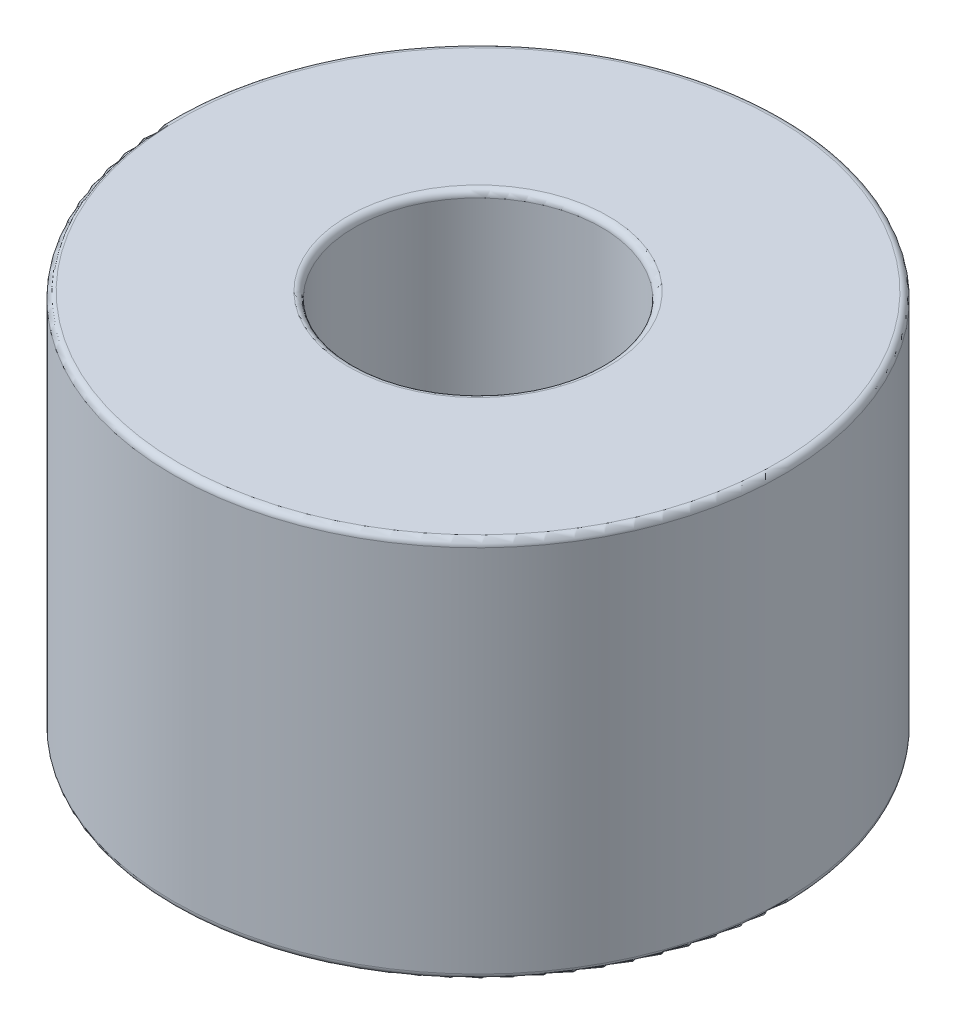
SolidWorks part; units mm, degrees
material "POLYURETHANE (11671)"
ref_plane "Front" through (0, 0, 0) normal (0, 0, 1) x (1, 0, 0)
ref_plane "Top" through (0, 0, 0) normal (0, 1, 0) x (1, 0, 0)
ref_plane "Right" through (0, 0, 0) normal (1, 0, 0) x (0, 0, -1)
sketch "Sketch1" plane through (0, 0, 0) normal (0, 1, 0) x (1, 0, 0)
  circle A0 centre (0, 0) radius 4.765
  circle A1 centre (0, 0) radius 11.75
  dimension "D1" = 9.53
  dimension "D2" = 23.5
extrude "Boss-Extrude1" add sketch "Sketch1" along normal blind 14.732
fillet "Fillet1" radius 0.254 4 edges at (0, 14.732, 4.765) (0, 14.732, 11.75) (0, 0, 4.765) (0, 0, 11.75)
